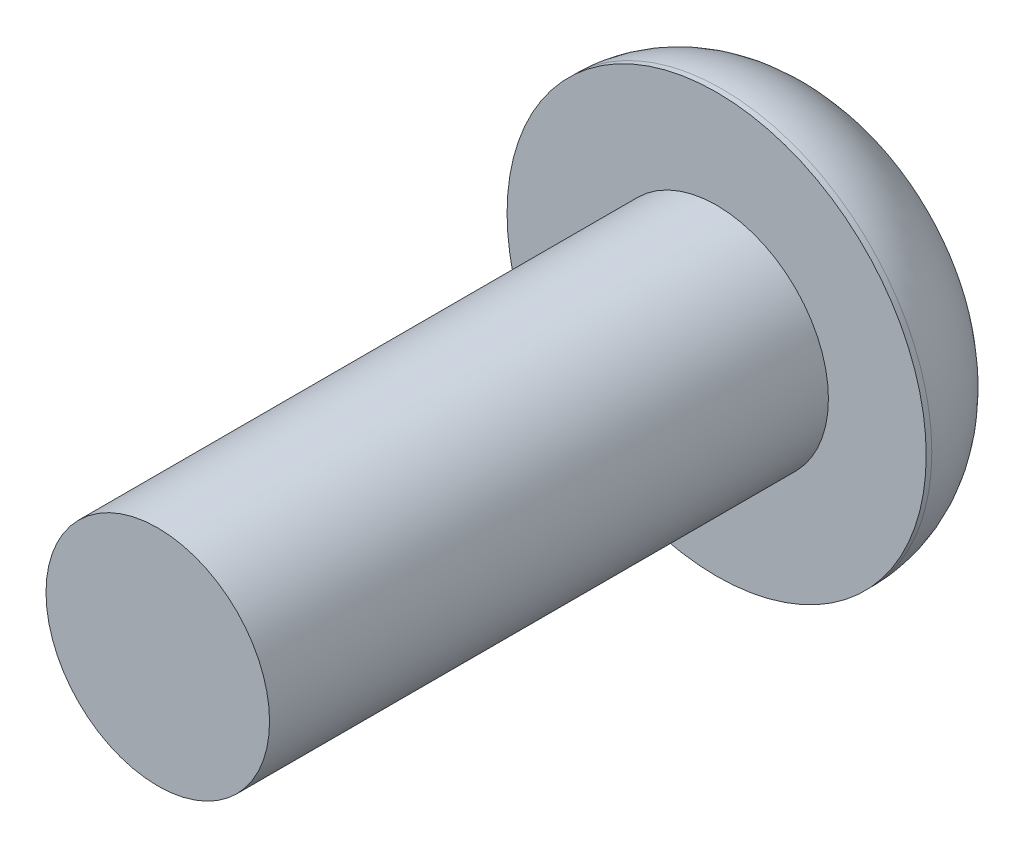
SolidWorks part; units mm, degrees
ref_plane "前视基准面" through (0, 0, 0) normal (0, 0, 1) x (1, 0, 0)
ref_plane "上视基准面" through (0, 0, 0) normal (0, 1, 0) x (1, 0, 0)
ref_plane "右视基准面" through (0, 0, 0) normal (1, 0, 0) x (0, 0, -1)
sketch "草图1" plane through (0, 0, 0) normal (0, 0, 1) x (1, 0, 0)
  circle A0 centre (0, 0) radius 2
extrude "凸台-拉伸1" add sketch "草图1" along normal blind 10
sketch "草图2" plane through (0, 0, 0) normal (0, 0, -1) x (-1, 0, 0)
  circle A0 centre (0, 0) radius 3.75
extrude "凸台-拉伸2" add sketch "草图2" along normal blind 2.1
fillet "圆角1" radius 2 1 edges at (-3.75, 0, -2.1)
